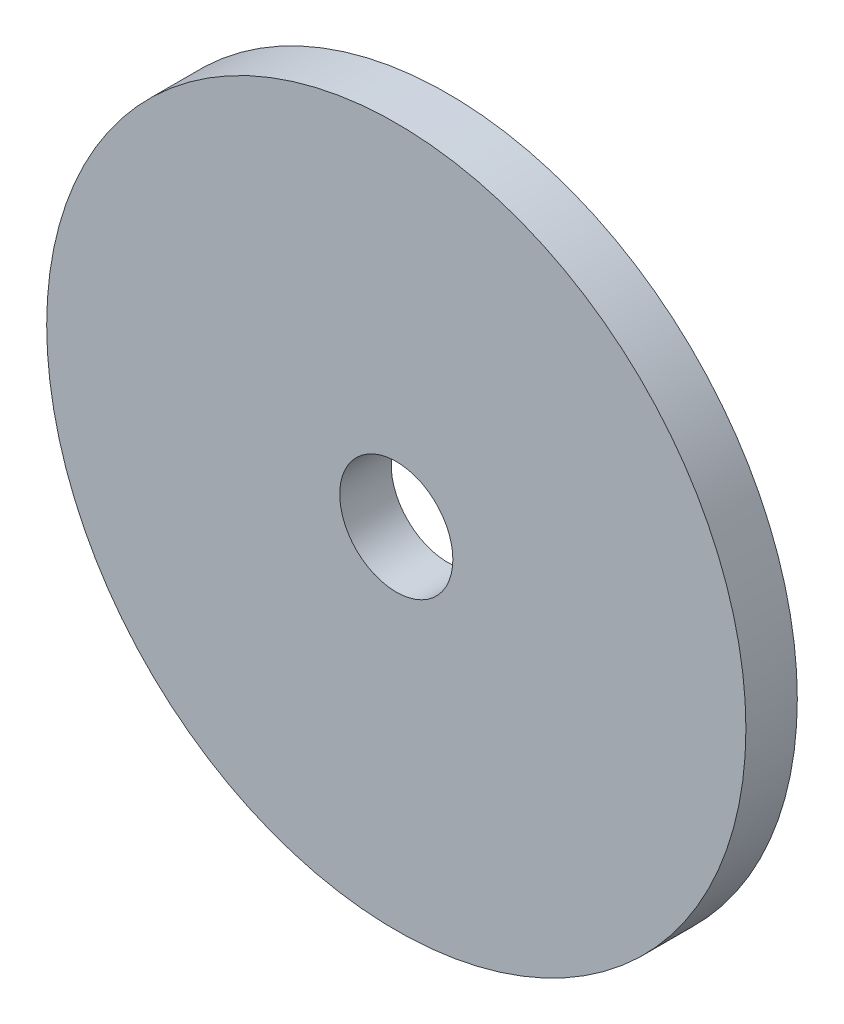
SolidWorks part; units mm, degrees
material "AISI 316 Нержавеющая сталь, лист (SS)"
ref_plane "Спереди" through (0, 0, 0) normal (0, 0, 1) x (1, 0, 0)
ref_plane "Сверху" through (0, 0, 0) normal (0, 1, 0) x (1, 0, 0)
ref_plane "Справа" through (0, 0, 0) normal (1, 0, 0) x (0, 0, -1)
sketch "Эскиз1" plane through (0, 0, 0) normal (0, 0, 1) x (1, 0, 0)
  circle A0 centre (0, 0) radius 34
  circle A1 centre (0, 0) radius 5.5
  dimension "D1" = 68
  dimension "D2" = 11
extrude "Бобышка-Вытянуть1" add sketch "Эскиз1" along normal blind 5
